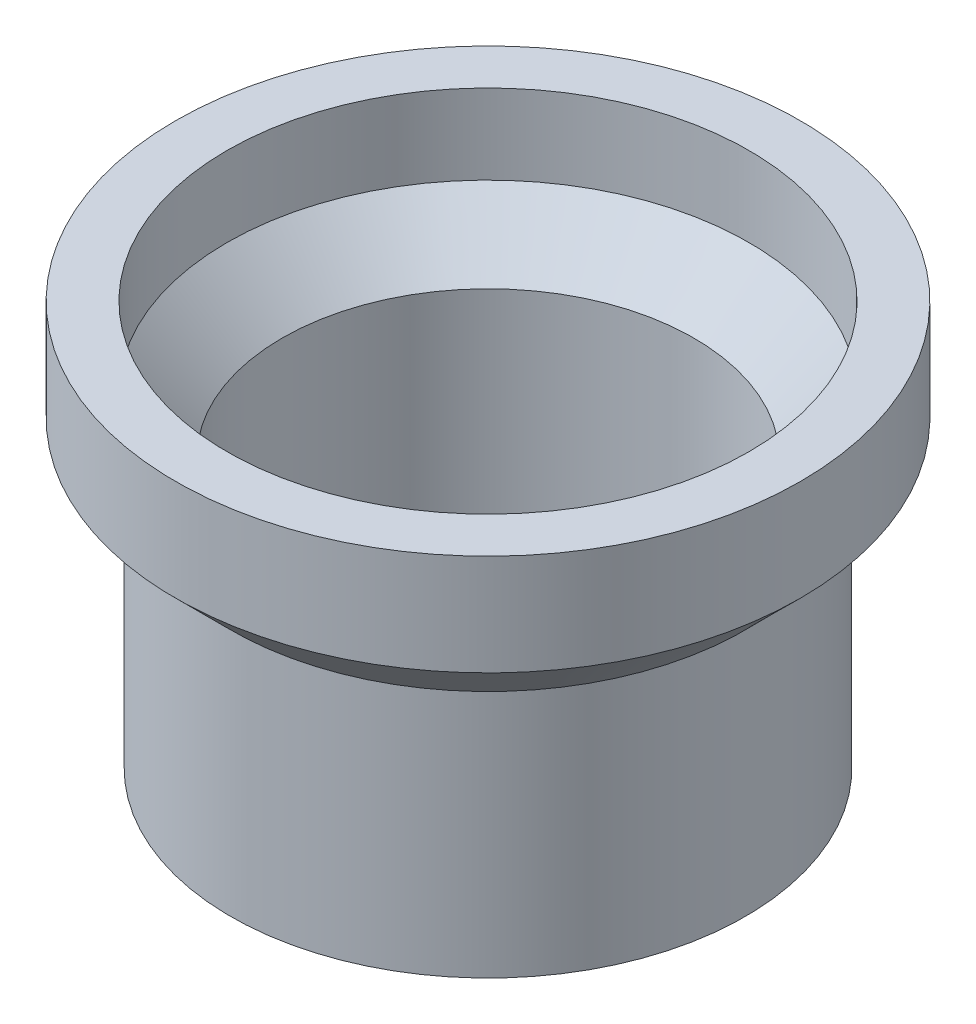
SolidWorks part; units mm, degrees
ref_plane "Płaszczyzna przednia" through (0, 0, 0) normal (0, 0, 1) x (1, 0, 0)
ref_plane "Płaszczyzna górna" through (0, 0, 0) normal (0, 1, 0) x (1, 0, 0)
ref_plane "Płaszczyzna prawa" through (0, 0, 0) normal (1, 0, 0) x (0, 0, -1)
sketch "Sketch1" plane through (0, 0, 0) normal (0, 0, 1) x (1, 0, 0)
  line L0 (0, 16.2795) -> (0, -16.2795) construction
  line L1 (17, 0) -> (17, -5.5)
  line L2 (14, -8.5) -> (14, -22)
  line L3 (17, -5.5) -> (14, -8.5)
  line L4 (14.2, 0) -> (14.2, -4.3402)
  line L5 (14.2, -4.3402) -> (11.2, -7.3402)
  line L6 (11.2, -7.3402) -> (11.2, -22)
  line L7 (11.2, -22) -> (14, -22)
  line L8 (14.2, 0) -> (17, 0)
  point P3 (0, 0)
  point P12 (15.6, 0)
  dimension "D1" = 5.5
  dimension "D2" = 17
  dimension "D3" = 14
  dimension "D4" = 3
  dimension "D5" = 22
  dimension "D6" = 11.2
revolve "Revolve1" add sketch "Sketch1" angle 360 about L0
chamfer "Chamfer1" distance 2 angle 45 1 edges at (-11.2, -22, 0)
